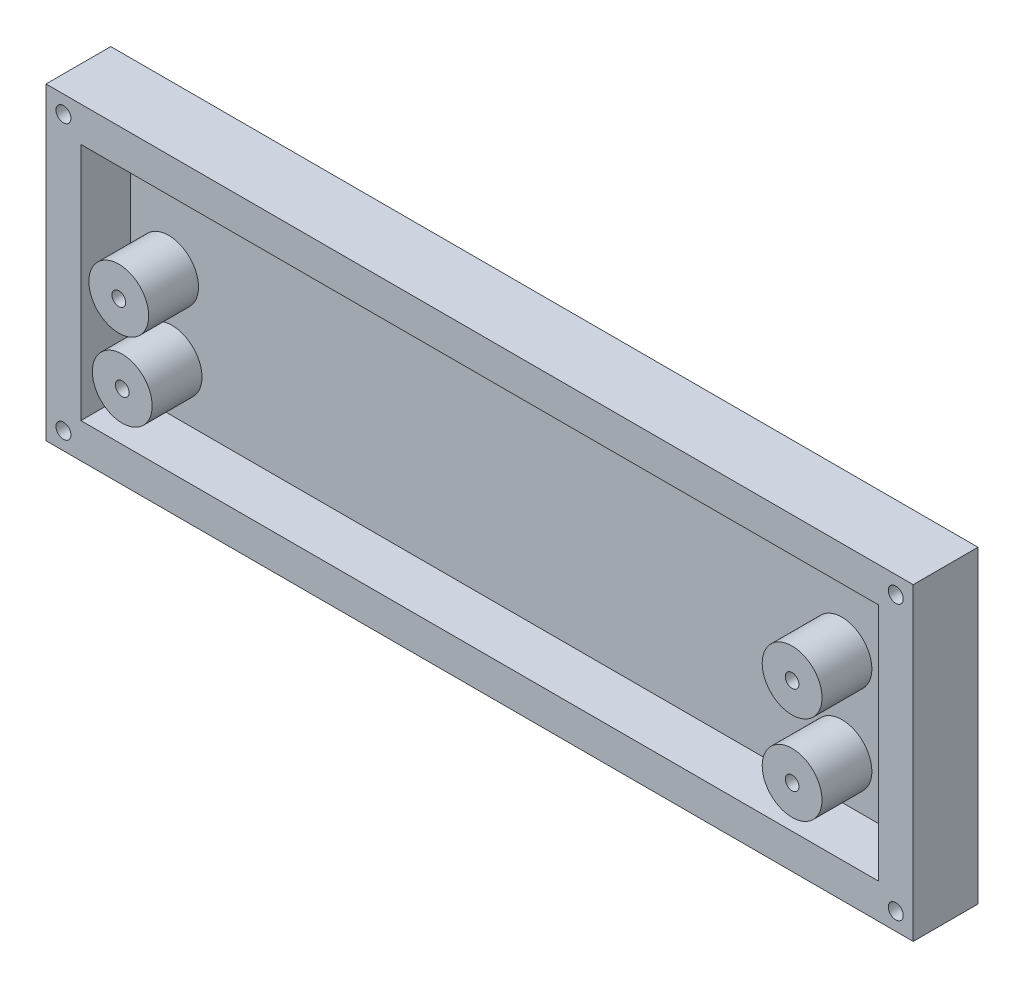
SolidWorks part; units mm, degrees
ref_plane "Přední rovina" through (0, 0, 0) normal (0, 0, 1) x (1, 0, 0)
ref_plane "Horní rovina" through (0, 0, 0) normal (0, 1, 0) x (1, 0, 0)
ref_plane "Pravá rovina" through (0, 0, 0) normal (1, 0, 0) x (0, 0, -1)
sketch "Skica1" plane through (0, 0, 0) normal (0, 0, 1) x (1, 0, 0)
  line L1 (0, 0) -> (160, 0)
  line L2 (0, 0) -> (0, 48)
  line L3 (0, 48) -> (160, 48)
  line L4 (160, 0) -> (160, 48)
  dimension "D1" = 48
  dimension "D2" = 160
extrude "Přidat vysunutím1" add sketch "Skica1" along normal blind 3
sketch "Skica3" plane through (0, 0, 0) normal (0, 0, -1) x (-1, 0, 0)
  line L1 (0, 0) -> (-160, 0)
  line L2 (0, 0) -> (0, 48)
  line L3 (0, 48) -> (-160, 48)
  line L4 (-160, 0) -> (-160, 48)
  line L12 (3, -3) -> (3, 51)
  line L13 (-163, -3) -> (3, -3)
  line L14 (-163, 51) -> (-163, -3)
  line L15 (3, 51) -> (-163, 51)
  line L16 (3, -3) -> (3, 51)
  line L17 (-163, -3) -> (3, -3)
  line L18 (-163, 51) -> (-163, -3)
  line L19 (3, 51) -> (-163, 51)
  circle A0 centre (-8.3, 9.7) radius 1.375
  circle A1 centre (-7.6, 25) radius 1.375
  circle A2 centre (-142.7, 26.2) radius 1.375
  circle A3 centre (-142.7, 8.4) radius 1.375
  circle A4 centre (-7.6, 25) radius 6
  circle A5 centre (-8.3, 9.7) radius 6
  circle A6 centre (-142.7, 26.2) radius 6
  circle A7 centre (-142.7, 8.4) radius 6
  dimension "D2" = 2.75
  dimension "D3" = 12
  dimension "D4" = 8.3
  dimension "D5" = 9.7
  dimension "D6" = 7.6
  dimension "D7" = 25
  dimension "D8" = 17.3
  dimension "D10" = 26.2
  dimension "D11" = 8.4
  dimension "D1" = 3
extrude "stojny k PCB" add sketch "Skica3" against normal blind 13 contours A4 A1 | A5 A0 | A6 A2 | A7 A3
sketch "Skica5" plane through (0, 0, 0) normal (0, 0, -1) x (-1, 0, 0)
  line L1 (0, 48) -> (-160, 48)
  line L2 (0, 48) -> (0, 0)
  line L3 (0, 0) -> (-160, 0)
  line L4 (-160, 48) -> (-160, 0)
  line L8 (7, -7) -> (7, 55)
  line L10 (7, -7) -> (7, 55)
  line L12 (-167, -7) -> (7, -7)
  line L14 (-167, -7) -> (7, -7)
  line L20 (-167, 55) -> (-167, -7)
  line L21 (-167, 55) -> (-167, -7)
  line L22 (7, 55) -> (-167, 55)
  line L23 (7, 55) -> (-167, 55)
  dimension "D1" = 7
extrude "Přidat vysunutím3" add sketch "Skica5" against normal blind 13
sketch "Skica7" plane through (0, 0, 13) normal (0, 0, 1) x (1, 0, 0)
  line L0 (167, -7) -> (-7, -7) construction
  line L2 (-7, -7) -> (-7, 55) construction
  line L3 (-7, 55) -> (167, 55) construction
  line L4 (167, 55) -> (167, -7) construction
  circle A0 centre (-3.5, -3.5) radius 1.5
  circle A1 centre (-3.5, 51.5) radius 1.5
  circle A2 centre (163.5, -3.5) radius 1.5
  circle A3 centre (163.5, 51.5) radius 1.5
  dimension "D1" = 3
  dimension "D2" = 3.5
  dimension "D3" = 3.5
  dimension "D4" = 3.5
  dimension "D5" = 3.5
extrude "Odebrat vysunutím2" cut sketch "Skica7" against normal through all both and the other way through all
